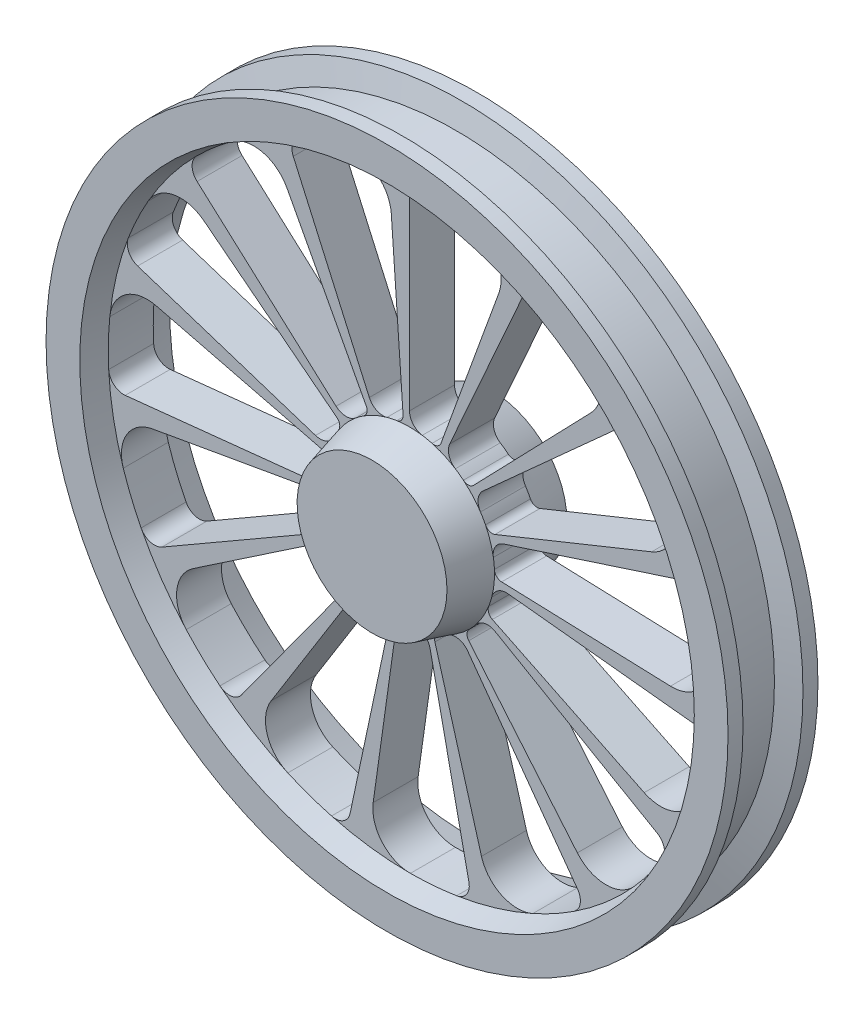
SolidWorks part; units mm, degrees
material "1060 Alloy"
ref_plane "Front Plane" through (0, 0, 0) normal (0, 0, 1) x (1, 0, 0)
ref_plane "Top Plane" through (0, 0, 0) normal (0, 1, 0) x (1, 0, 0)
ref_plane "Right Plane" through (0, 0, 0) normal (1, 0, 0) x (0, 0, -1)
sketch "Sketch1" plane through (0, 0, 0) normal (1, 0, 0) x (0, 0, -1)
  line L0 (-1000, 0) -> (49000, 0) construction
  line L29 (-80, 0) -> (80, 0)
  line L30 (80, 0) -> (80, 100)
  line L31 (80, 100) -> (30, 113.3975)
  line L32 (30, 113.3975) -> (30, 401.9615)
  line L33 (30, 401.9615) -> (60, 410)
  line L34 (60, 410) -> (60, 455)
  line L37 (31.9615, 425) -> (-31.9615, 425)
  line L38 (-31.9615, 425) -> (-40, 455)
  line L39 (-40, 455) -> (-60, 455)
  line L40 (-60, 455) -> (-60, 410)
  line L41 (-60, 410) -> (-30, 401.9615)
  line L42 (-30, 401.9615) -> (-30, 113.3975)
  line L43 (-30, 113.3975) -> (-80, 100)
  line L44 (-80, 100) -> (-80, 0)
  line L45 (31.9615, 425) -> (40, 455)
  line L46 (40, 455) -> (60, 455)
  point P18 (0, 0)
  point P23 (45, 405.9808)
  point P24 (0, 425)
  dimension "D1" = 160
  dimension "D2" = 60
  dimension "D3" = 105
  dimension "D4" = 200
  dimension "D5" = 120
  dimension "D6" = 105
  dimension "D7" = 20
  dimension "D8" = 910
  dimension "D9" = 30
  dimension "D10" = 105
  dimension "D11" = 45
revolve "Revolve1" add sketch "Sketch1" angle 360 about L0
sketch "Sketch2" plane through (0, 0, 30) normal (0, 0, 1) x (1, 0, 0)
  line L32 (0, 131.8897) -> (0, 381.4376)
  line L33 (119.157, 327.3813) -> (42.0656, 115.5743)
  line L34 (242.0133, 250.6122) -> (85.4371, 88.4728)
  line L35 (53.6444, 120.4872) -> (155.1446, 348.4605)
  line L36 (323.0233, 130.5099) -> (114.0358, 46.0735)
  line L37 (98.0131, 88.2514) -> (283.4633, 255.2315)
  line L38 (348.1797, -12.1587) -> (122.9167, -4.2923)
  line L39 (125.4345, 40.7561) -> (362.7687, 117.8707)
  line L40 (313.1326, -152.725) -> (110.5441, -53.916)
  line L41 (131.1672, -13.7862) -> (379.348, -39.8711)
  line L42 (223.942, -266.8837) -> (79.0575, -94.217)
  line L43 (114.2198, -65.9448) -> (330.3346, -190.7188)
  line L44 (96.0298, -334.8958) -> (33.9011, -118.2271)
  line L45 (77.5228, -106.701) -> (224.2034, -308.5895)
  line L46 (-48.4868, -345.0014) -> (-17.1171, -121.7947)
  line L47 (27.4214, -129.0076) -> (79.3053, -373.1022)
  line L48 (-184.6196, -295.4531) -> (-65.1756, -104.3028)
  line L49 (-27.4214, -129.0076) -> (-79.3053, -373.1022)
  line L50 (-288.83, -194.8183) -> (-101.9647, -68.776)
  line L51 (-77.5228, -106.701) -> (-224.2034, -308.5895)
  line L52 (-343.099, -60.4976) -> (-121.1231, -21.3573)
  line L53 (-114.2198, -65.9448) -> (-330.3346, -190.7188)
  line L54 (-338.0432, 84.2836) -> (-119.3382, 29.7544)
  line L55 (-131.1672, -13.7862) -> (-379.348, -39.8711)
  line L56 (-274.5366, 214.4915) -> (-96.9187, 75.7212)
  line L57 (-125.4345, 40.7561) -> (-362.7687, 117.8707)
  line L58 (-163.5601, 307.6118) -> (-57.7411, 108.5951)
  line L59 (-98.0131, 88.2514) -> (-283.4633, 255.2315)
  line L60 (-24.3026, 347.5432) -> (-8.5795, 122.692)
  line L61 (-53.6444, 120.4872) -> (-155.1446, 348.4605)
  line L62 (0, 0) -> (30.0212, 109.3513) construction
  line L63 (0, 0) -> (71.903, 87.6867) construction
  arc A0 (30.0212, 109.3513) -> (17.0014, 112.1157) centre (0, 0) ccw
  arc A1 (17.0014, 112.1157) -> (0, 131.8897) centre (20, 131.8897) cw
  arc A32 (0, 381.4376) -> (21.0472, 401.4101) centre (20, 381.4376) cw
  circle A33 centre (0, 0) radius 401.9615 construction
  arc A34 (21.0472, 401.4101) -> (82.4253, 393.4198) centre (0, 0) cw
  arc A35 (82.4253, 393.4198) -> (119.157, 327.3813) centre (72.1724, 344.4823) cw
  arc A36 (42.0656, 115.5743) -> (30.0212, 109.3513) centre (32.6687, 118.9945) cw
  circle A37 centre (0, 0) radius 113.3975 construction
  arc A38 (85.4371, 88.4728) -> (71.903, 87.6867) centre (78.2437, 95.4193) cw
  arc A39 (71.903, 87.6867) -> (61.1332, 95.5077) centre (0, 0) ccw
  arc A40 (61.1332, 95.5077) -> (53.6444, 120.4872) centre (71.9153, 112.3525) cw
  arc A41 (155.1446, 348.4605) -> (182.4958, 358.1457) centre (173.4155, 340.3258) cw
  arc A42 (182.4958, 358.1457) -> (235.3175, 325.8815) centre (0, 0) cw
  arc A43 (235.3175, 325.8815) -> (242.0133, 250.6122) centre (206.0464, 285.3451) cw
  arc A44 (114.0358, 46.0735) -> (101.352, 50.8602) centre (110.2898, 55.3453) cw
  arc A45 (101.352, 50.8602) -> (94.6944, 62.3855) centre (0, 0) ccw
  arc A46 (94.6944, 62.3855) -> (98.0131, 88.2514) centre (111.3957, 73.3885) cw
  arc A47 (283.4633, 255.2315) -> (312.3892, 252.9547) centre (296.846, 240.3686) cw
  arc A48 (312.3892, 252.9547) -> (347.5212, 201.9953) centre (0, 0) cw
  arc A49 (347.5212, 201.9953) -> (323.0233, 130.5099) centre (304.293, 176.8691) cw
  arc A50 (122.9167, -4.2923) -> (113.2763, 5.2395) centre (123.2657, 5.7016) cw
  arc A51 (113.2763, 5.2395) -> (111.8821, 18.4763) centre (0, 0) ccw
  arc A52 (111.8821, 18.4763) -> (125.4345, 40.7561) centre (131.6149, 21.735) cw
  arc A53 (362.7687, 117.8707) -> (388.2677, 104.0254) centre (368.949, 98.8496) cw
  arc A54 (388.2677, 104.0254) -> (399.6353, 43.1823) centre (0, 0) cw
  arc A55 (399.6353, 43.1823) -> (348.1797, -12.1587) centre (349.9246, 37.8108) cw
  arc A56 (110.5441, -53.916) -> (105.6142, -41.2871) centre (114.9278, -44.928) cw
  arc A57 (105.6142, -41.2871) -> (109.7244, -28.6276) centre (0, 0) ccw
  arc A58 (109.7244, -28.6276) -> (131.1672, -13.7862) centre (129.0766, -33.6767) cw
  arc A59 (379.348, -39.8711) -> (397.0111, -62.8907) centre (377.2574, -59.7615) cw
  arc A60 (397.0111, -62.8907) -> (382.6488, -123.0973) centre (0, 0) cw
  arc A61 (382.6488, -123.0973) -> (313.1326, -152.725) centre (335.0511, -107.7853) cw
  arc A62 (79.0575, -94.217) -> (79.6904, -80.6748) centre (86.7179, -87.7892) cw
  arc A63 (79.6904, -80.6748) -> (88.5943, -70.7815) centre (0, 0) ccw
  arc A64 (88.5943, -70.7815) -> (114.2198, -65.9448) centre (104.2198, -83.2653) cw
  arc A65 (330.3346, -190.7188) -> (337.1077, -218.9325) centre (320.3346, -208.0393) cw
  arc A66 (337.1077, -218.9325) -> (299.4989, -268.0923) centre (0, 0) cw
  arc A67 (299.4989, -268.0923) -> (223.942, -266.8837) centre (262.2442, -234.7443) cw
  arc A68 (33.9011, -118.2271) -> (39.9874, -106.1131) centre (43.5137, -115.4707) cw
  arc A69 (39.9874, -106.1131) -> (52.1455, -100.6967) centre (0, 0) ccw
  arc A70 (52.1455, -100.6967) -> (77.5228, -106.701) centre (61.3425, -118.4567) cw
  arc A71 (224.2034, -308.5895) -> (218.9154, -337.1189) centre (208.023, -320.3452) cw
  arc A72 (218.9154, -337.1189) -> (164.5629, -366.7317) centre (0, 0) cw
  arc A73 (164.5629, -366.7317) -> (96.0298, -334.8958) centre (144.0929, -321.1139) cw
  arc A74 (-17.1171, -121.7947) -> (-6.6298, -113.2035) centre (-7.2144, -123.1864) cw
  arc A75 (-6.6298, -113.2035) -> (6.6802, -113.2005) centre (0, 0) ccw
  arc A76 (6.6802, -113.2005) -> (27.4214, -129.0076) centre (7.8585, -133.1658) cw
  arc A77 (79.3053, -373.1022) -> (62.8706, -397.0143) centre (59.7424, -377.2605) cw
  arc A78 (62.8706, -397.0143) -> (1.1725, -401.9598) centre (0, 0) cw
  arc A79 (1.1725, -401.9598) -> (-48.4868, -345.0014) centre (1.0266, -351.96) cw
  arc A80 (-65.1756, -104.3028) -> (-52.1006, -100.72) centre (-56.6951, -109.602) cw
  arc A81 (-52.1006, -100.72) -> (-39.9401, -106.1309) centre (0, 0) ccw
  arc A82 (-39.9401, -106.1309) -> (-27.4214, -129.0076) centre (-46.9844, -124.8493) cw
  arc A83 (-79.3053, -373.1022) -> (-104.0451, -388.2624) centre (-98.8683, -368.944) cw
  arc A84 (-104.0451, -388.2624) -> (-162.4207, -367.6854) centre (0, 0) cw
  arc A85 (-162.4207, -367.6854) -> (-184.6196, -295.4531) centre (-142.2172, -321.949) cw
  arc A86 (-101.9647, -68.776) -> (-88.5628, -70.821) centre (-96.3727, -77.0664) cw
  arc A87 (-88.5628, -70.821) -> (-79.6544, -80.7103) centre (0, 0) ccw
  arc A88 (-79.6544, -80.7103) -> (-77.5228, -106.701) centre (-93.7031, -94.9453) cw
  arc A89 (-224.2034, -308.5895) -> (-252.9705, -312.3764) centre (-240.3837, -296.8338) cw
  arc A90 (-252.9705, -312.3764) -> (-297.9298, -269.8349) centre (0, 0) cw
  arc A91 (-297.9298, -269.8349) -> (-288.83, -194.8183) centre (-260.8703, -236.2702) cw
  arc A92 (-121.1231, -21.3573) -> (-109.7116, -28.6765) centre (-119.3866, -31.2053) cw
  arc A93 (-109.7116, -28.6765) -> (-105.5958, -41.3342) centre (0, 0) ccw
  arc A94 (-105.5958, -41.3342) -> (-114.2198, -65.9448) centre (-124.2198, -48.6243) cw
  arc A95 (-330.3346, -190.7188) -> (-358.155, -182.4776) centre (-340.3346, -173.3983) cw
  arc A96 (-358.155, -182.4776) -> (-381.9242, -125.3275) centre (0, 0) cw
  arc A97 (-381.9242, -125.3275) -> (-343.099, -60.4976) centre (-334.4166, -109.738) cw
  arc A98 (-119.3382, 29.7544) -> (-111.8903, 18.4265) centre (-121.7574, 20.0514) cw
  arc A99 (-111.8903, 18.4265) -> (-113.2787, 5.189) centre (0, 0) ccw
  arc A100 (-113.2787, 5.189) -> (-131.1672, -13.7862) centre (-133.2577, 6.1042) cw
  arc A101 (-379.348, -39.8711) -> (-401.4112, -21.0269) centre (-381.4386, -19.9806) cw
  arc A102 (-401.4112, -21.0269) -> (-399.8804, 40.8502) centre (0, 0) cw
  arc A103 (-399.8804, 40.8502) -> (-338.0432, 84.2836) centre (-350.1393, 35.7688) cw
  arc A104 (-96.9187, 75.7212) -> (-94.7222, 62.3433) centre (-103.0753, 67.8411) cw
  arc A105 (-94.7222, 62.3433) -> (-101.3747, 50.815) centre (0, 0) ccw
  arc A106 (-101.3747, 50.815) -> (-125.4345, 40.7561) centre (-119.2542, 59.7773) cw
  arc A107 (-362.7687, 117.8707) -> (-375.2598, 144.0596) centre (-356.5883, 136.8918) cw
  arc A108 (-375.2598, 144.0596) -> (-348.6936, 199.9645) centre (0, 0) cw
  arc A109 (-348.6936, 199.9645) -> (-274.5366, 214.4915) centre (-305.3196, 175.0909) cw
  arc A110 (-57.7411, 108.5951) -> (-61.1757, 95.4804) centre (-66.5705, 103.9004) cw
  arc A111 (-61.1757, 95.4804) -> (-71.942, 87.6546) centre (0, 0) ccw
  arc A112 (-71.942, 87.6546) -> (-98.0131, 88.2514) centre (-84.6305, 103.1143) cw
  arc A113 (-283.4633, 255.2315) -> (-284.2225, 284.2369) centre (-270.0807, 270.0944) cw
  arc A114 (-284.2225, 284.2369) -> (-237.2146, 324.5032) centre (0, 0) cw
  arc A115 (-237.2146, 324.5032) -> (-163.5601, 307.6118) centre (-207.7075, 284.1382) cw
  arc A116 (-8.5795, 122.692) -> (-17.0514, 112.1081) centre (-18.5551, 121.9944) cw
  arc A117 (-17.0514, 112.1081) -> (-30.07, 109.3379) centre (0, 0) ccw
  arc A118 (-30.07, 109.3379) -> (-53.6444, 120.4872) centre (-35.3734, 128.6219) cw
  arc A119 (-155.1446, 348.4605) -> (-144.0406, 375.2671) centre (-136.8737, 356.5953) cw
  arc A120 (-144.0406, 375.2671) -> (-84.719, 392.9323) centre (0, 0) cw
  arc A121 (-84.719, 392.9323) -> (-24.3026, 347.5432) centre (-74.1808, 344.0554) cw
  point P70 (0, 0)
  dimension "D1" = 20
  dimension "D3" = 50
  dimension "D2" = 10
  dimension "D4" = 20
  dimension "D5" = 20
  dimension "D7" = 24
  dimension "D6" = 15
extrude "Cut-Extrude1" cut sketch "Sketch2" against normal through all
